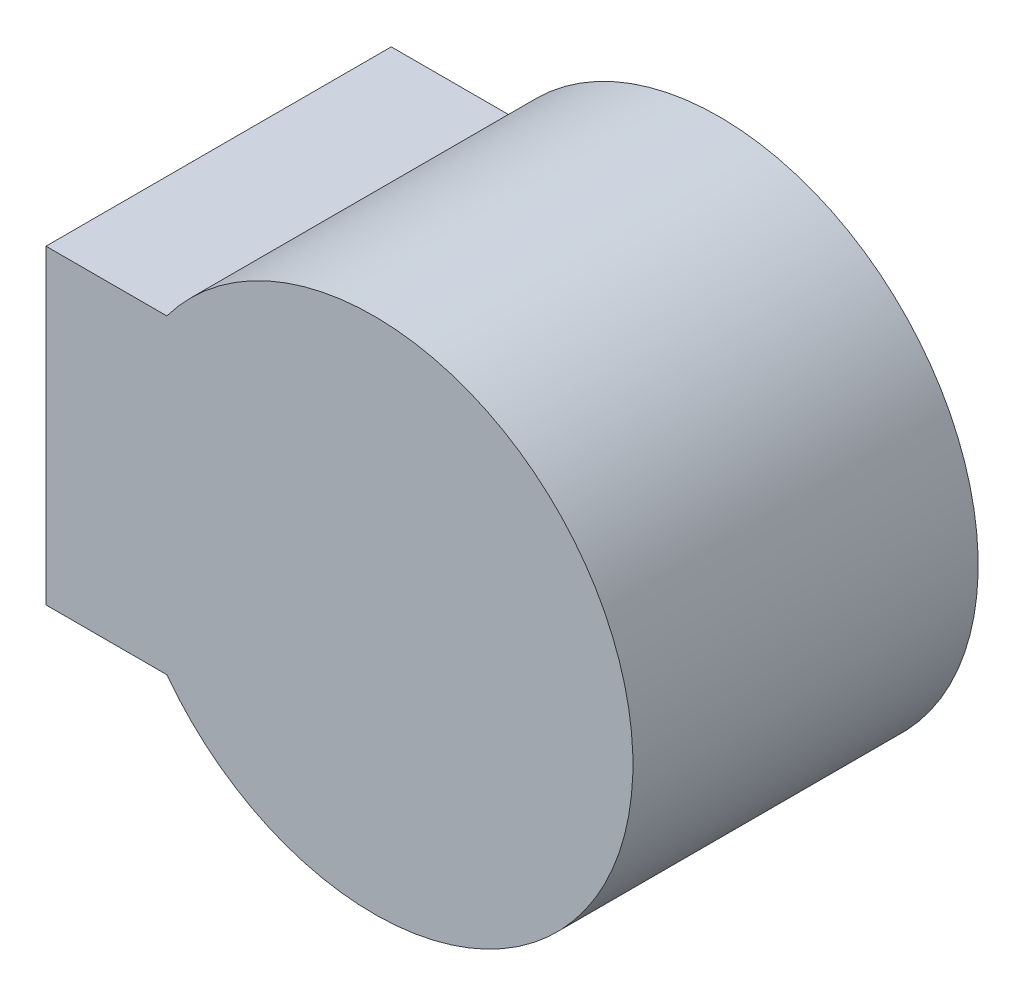
SolidWorks part; units mm, degrees
ref_plane "Alzado" through (0, 0, 0) normal (0, 0, 1) x (1, 0, 0)
ref_plane "Planta" through (0, 0, 0) normal (0, 1, 0) x (1, 0, 0)
ref_plane "Vista lateral" through (0, 0, 0) normal (1, 0, 0) x (0, 0, -1)
sketch "Croquis1" plane through (0, 0, 0) normal (0, 0, 1) x (1, 0, 0)
  line L0 (0, 4.5) -> (0, -4.5) construction
  line L1 (-9.5, -4.5) -> (0, -4.5) construction
  line L2 (-9.5, -4.5) -> (-9.5, 4.5)
  line L3 (-9.5, 4.5) -> (0, 4.5) construction
  line L5 (-9.5, 4.5) -> (-6, 4.5)
  line L6 (-9.5, -4.5) -> (-6, -4.5)
  arc A0 (-6, -4.5) -> (-6, 4.5) centre (0, 0) ccw
  point P3 (0, 0)
  dimension "D1" = 15
  dimension "D2" = 9.5
  dimension "D3" = 9
extrude "Saliente-Extruir1" add sketch "Croquis1" along normal blind 10
